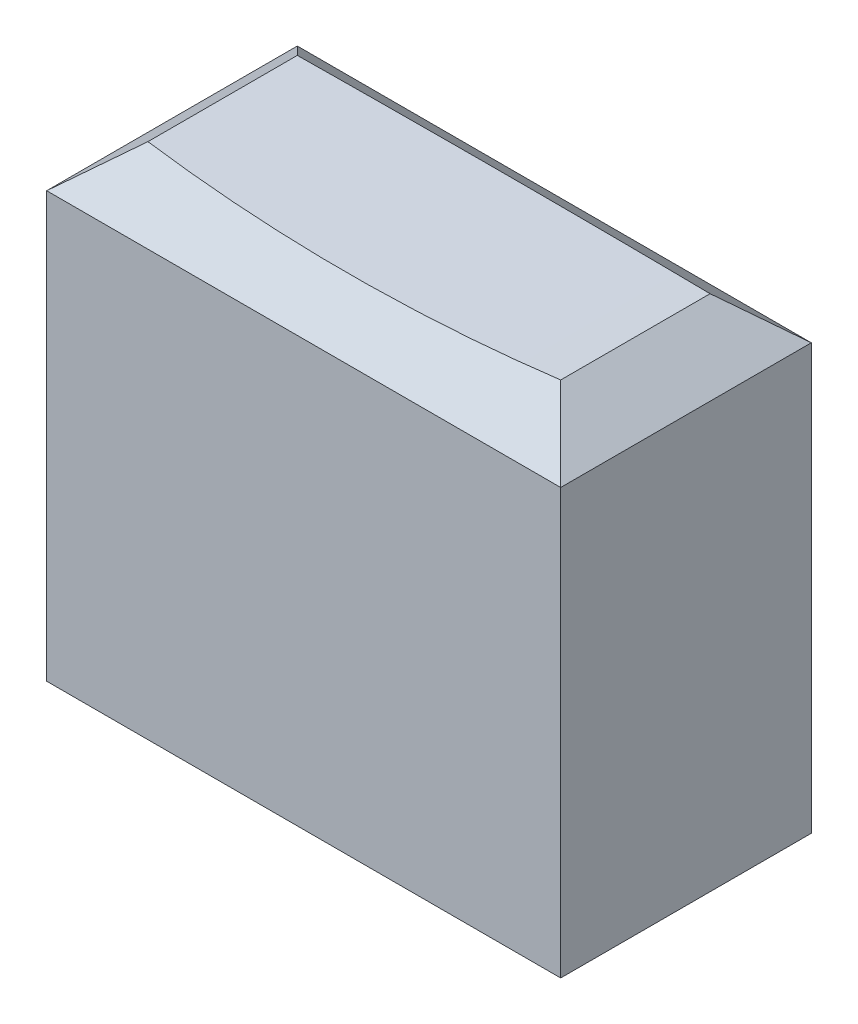
SolidWorks part; units mm, degrees
ref_plane "Front Plane" through (0, 0, 0) normal (0, 0, 1) x (1, 0, 0)
ref_plane "Top Plane" through (0, 0, 0) normal (0, 1, 0) x (1, 0, 0)
ref_plane "Right Plane" through (0, 0, 0) normal (1, 0, 0) x (0, 0, -1)
sketch "Sketch1" plane through (0, 0, 0) normal (0, 1, 0) x (1, 0, 0)
  line L1 (-6.05, 2.95) -> (6.05, 2.95)
  line L2 (-6.05, 2.95) -> (-6.05, -2.95)
  line L3 (-6.05, -2.95) -> (6.05, -2.95)
  line L4 (6.05, 2.95) -> (6.05, -2.95)
  point P4 (6.05, 0)
  point P6 (0, 2.95)
  dimension "D1" = 12.1
  dimension "D2" = 5.9
extrude "Boss-Extrude1" add sketch "Sketch1" along normal blind 11
chamfer "Chamfer1" distance 1 angle 50 4 edges at (0, 11, -2.95) (6.05, 11, 0) (0, 11, 2.95) (-6.05, 11, 0)
sketch "Sketch6" plane through (0, 0, 2.95) normal (0, 0, 1) x (1, 0, 0)
  line L0 (-4.8582, 11) -> (4.8582, 11) construction
  line L1 (-4.8582, 11) -> (4.8582, 11)
  line L2 (-4.8582, 10.85) -> (4.8582, 10.85) construction
  arc A0 (-4.8582, 11) -> (4.8582, 11) centre (0, 89.6002) ccw
  dimension "D1" = 0.3
extrude "Cut-Extrude3" cut sketch "Sketch6" against normal through all
sketch "Sketch7" plane through (0, 0, 0) normal (0, -1, 0) x (1, 0, 0)
  line L0 (-2.05, -1) -> (-2.05, -2.45)
  line L1 (-5.55, 2.45) -> (-2.05, 2.45)
  line L2 (-5.55, 2.45) -> (-5.55, -2.45)
  line L3 (-5.55, -2.45) -> (-2.05, -2.45)
  line L4 (-2.05, 2.45) -> (-2.05, 1)
  line L5 (2.05, 2.45) -> (5.55, 2.45)
  line L6 (2.05, 2.45) -> (2.05, 1)
  line L7 (2.05, -2.45) -> (5.55, -2.45)
  line L8 (5.55, 2.45) -> (5.55, -2.45)
  line L9 (-1.65, 1.65) -> (1.65, 1.65)
  line L10 (-1.65, 1.65) -> (-1.65, 1)
  line L11 (-1.65, -1.65) -> (1.65, -1.65)
  line L12 (1.65, 1.65) -> (1.65, 1)
  line L13 (-2.05, 1) -> (-1.65, 1)
  line L15 (-2.05, -1) -> (-1.65, -1)
  line L17 (-1.65, -1) -> (-1.65, -1.65)
  line L18 (1.65, -1) -> (1.65, -1.65)
  line L19 (2.05, -1) -> (2.05, -2.45)
  line L20 (1.65, 1) -> (2.05, 1)
  line L21 (1.65, -1) -> (2.05, -1)
  line L22 (-6.05, 2.95) -> (6.05, 2.95) construction
  line L23 (6.05, -2.95) -> (-6.05, -2.95) construction
  line L24 (-6.05, -2.95) -> (-6.05, 2.95) construction
  line L25 (6.05, 2.95) -> (6.05, -2.95) construction
  dimension "D1" = 0.5
  dimension "D2" = 0.5
  dimension "D3" = 0.5
  dimension "D4" = 0.5
  dimension "D5" = 3.3
  dimension "D6" = 0.4
  dimension "D7" = 3.3
  dimension "D8" = 2
extrude "Cut-Extrude4" cut sketch "Sketch7" against normal blind 9
